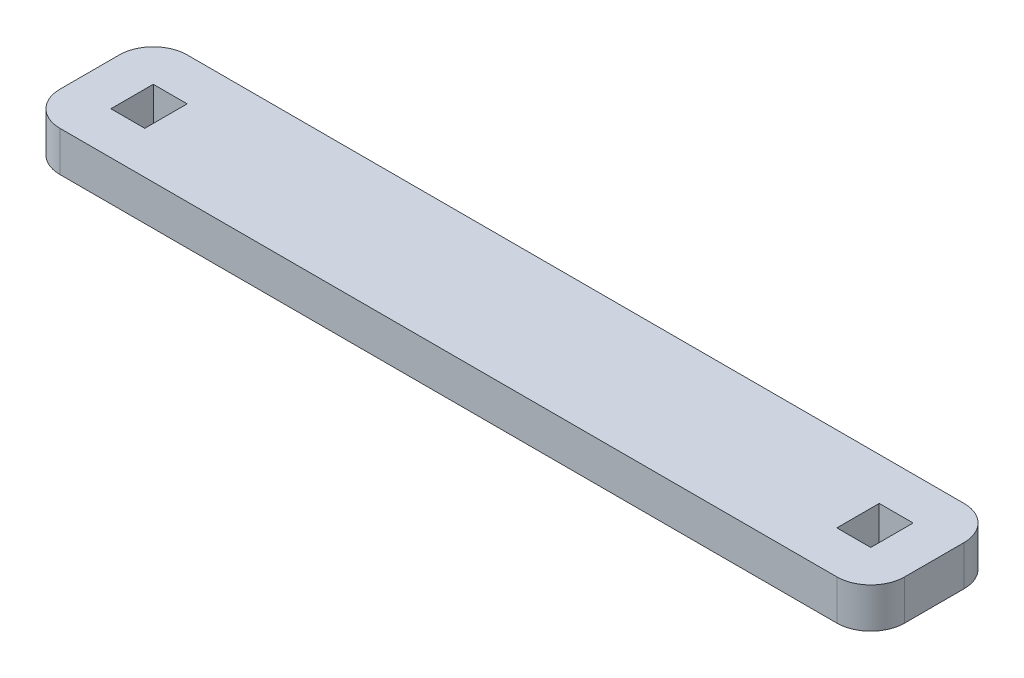
SolidWorks part; units mm, degrees
ref_plane "Front Plane" through (0, 0, 0) normal (0, 0, 1) x (1, 0, 0)
ref_plane "Top Plane" through (0, 0, 0) normal (0, 1, 0) x (1, 0, 0)
ref_plane "Right Plane" through (0, 0, 0) normal (1, 0, 0) x (0, 0, -1)
sketch "Sketch1" plane through (0, 0, 0) normal (0, 1, 0) x (1, 0, 0)
  line L0 (-27.178, 0) -> (27.178, 0) construction
  line L6 (31.623, -4.7625) -> (-31.623, -4.7625)
  line L7 (-25.908, -1.5875) -> (-28.448, -1.5875)
  line L8 (-25.908, -1.5875) -> (-25.908, 1.5875)
  line L9 (-25.908, 1.5875) -> (-28.448, 1.5875)
  line L10 (-28.448, -1.5875) -> (-28.448, 1.5875)
  line L11 (-25.908, -1.5875) -> (-28.448, 1.5875) construction
  line L12 (-25.908, 1.5875) -> (-28.448, -1.5875) construction
  line L13 (28.448, -1.5875) -> (25.908, -1.5875)
  line L14 (28.448, -1.5875) -> (28.448, 1.5875)
  line L15 (28.448, 1.5875) -> (25.908, 1.5875)
  line L16 (25.908, -1.5875) -> (25.908, 1.5875)
  line L17 (28.448, -1.5875) -> (25.908, 1.5875) construction
  line L18 (28.448, 1.5875) -> (25.908, -1.5875) construction
  line L19 (31.623, -4.7625) -> (31.623, 4.7625)
  line L20 (31.623, 4.7625) -> (-31.623, 4.7625)
  line L21 (-31.623, -4.7625) -> (-31.623, 4.7625)
  line L22 (31.623, -4.7625) -> (-31.623, 4.7625) construction
  line L23 (31.623, 4.7625) -> (-31.623, -4.7625) construction
  point P0 (0, 0)
  point P1 (0, 0)
  point P6 (-27.178, 0)
  point P11 (27.178, 0)
  dimension "D1" = 9.525
  dimension "D2" = 3.175
  dimension "D3" = 2.54
  dimension "D4" = 54.356
  dimension "D5" = 3.175
extrude "Boss-Extrude1" add sketch "Sketch1" along normal mid plane 3
fillet "Fillet1" radius 2.54 4 edges at (-31.623, 0, -4.7625) (31.623, 0, -4.7625) (31.623, 0, 4.7625) (-31.623, 0, 4.7625)
